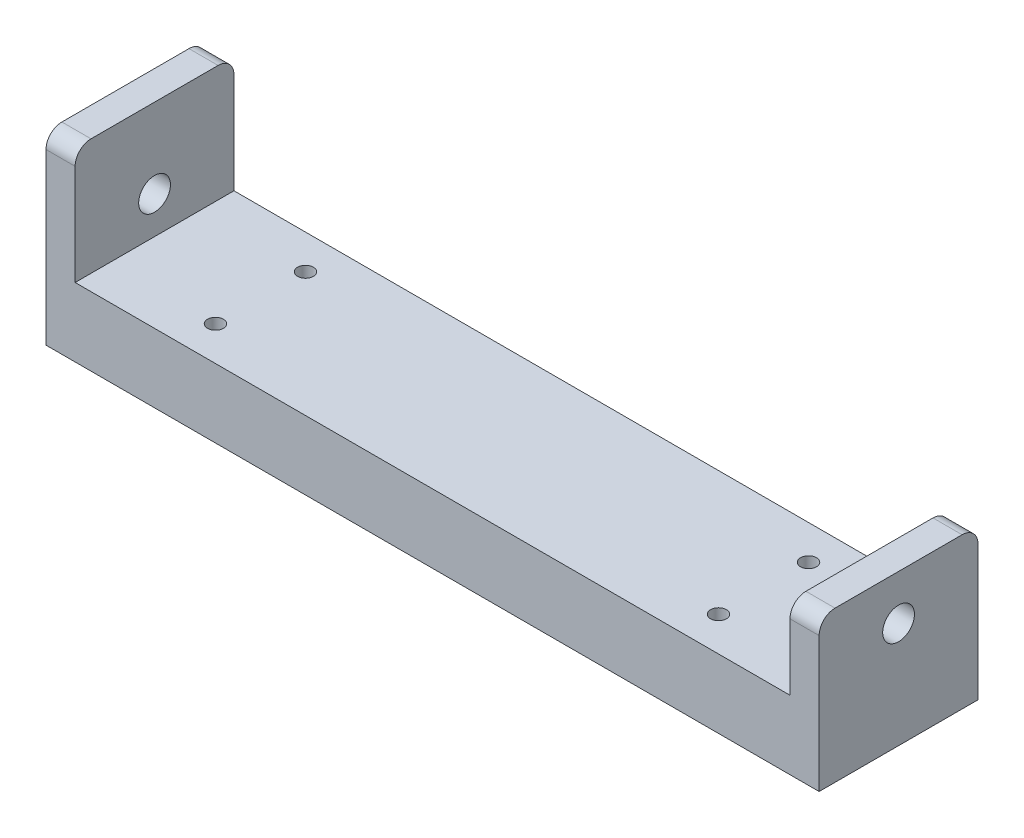
SolidWorks part; units mm, degrees
material "普通碳钢"
ref_plane "前视基准面" through (0, 0, 0) normal (0, 0, 1) x (1, 0, 0)
ref_plane "上视基准面" through (0, 0, 0) normal (0, 1, 0) x (1, 0, 0)
ref_plane "右视基准面" through (0, 0, 0) normal (1, 0, 0) x (0, 0, -1)
sketch "草图1" plane through (0, 0, 0) normal (0, 0, 1) x (1, 0, 0)
  line L0 (0, 0) -> (146, 0)
  line L1 (146, 0) -> (146, 28.5)
  line L2 (146, 28.5) -> (140.5, 28.5)
  line L3 (140.5, 28.5) -> (140.5, 13)
  line L4 (140.5, 13) -> (5.5, 13)
  line L5 (5.5, 13) -> (5.5, 35)
  line L6 (5.5, 35) -> (0, 35)
  line L7 (0, 35) -> (0, 0)
  dimension "D1" = 5.5
  dimension "D2" = 35
  dimension "D3" = 28.5
  dimension "D4" = 13
  dimension "D5" = 146
  dimension "D6" = 5.5
extrude "凸台-拉伸1" add sketch "草图1" along normal mid plane 30
sketch "草图2" plane through (0, 13, 0) normal (0, 1, 0) x (1, 0, 0)
  line L0 (0, 0) -> (146, 0) construction
  line L1 (146, -15) -> (146, 15) construction
  line L2 (73, 0) -> (73, 15) construction
  line L3 (140.5, 15) -> (5.5, 15) construction
  line L4 (5.5, -15) -> (5.5, 15) construction
  circle A0 centre (25.5, 8.5) radius 1.5
  circle A1 centre (120.5, 8.5) radius 1.5
  circle A2 centre (25.5, -8.5) radius 1.5
  circle A3 centre (120.5, -8.5) radius 1.5
  dimension "D3" = 3
  dimension "D1" = 8.5
  dimension "D2" = 20
extrude "切除-拉伸1" cut sketch "草图2" against normal up to next
fillet "圆角2" radius 3 4 edges at (143.25, 28.5, -15) (143.25, 28.5, 15) (2.75, 35, -15) (2.75, 35, 15)
sketch "草图3" plane through (0, 0, 0) normal (-1, 0, 0) x (0, 0, 1)
  line L0 (0, 35) -> (0, 0) construction
  line L1 (12, 35) -> (-12, 35) construction
  line L2 (15, 0) -> (-15, 0) construction
  circle A0 centre (0, 20) radius 3
  dimension "D2" = 6
  dimension "D1" = 20
extrude "切除-拉伸2" cut sketch "草图3" against normal through all
